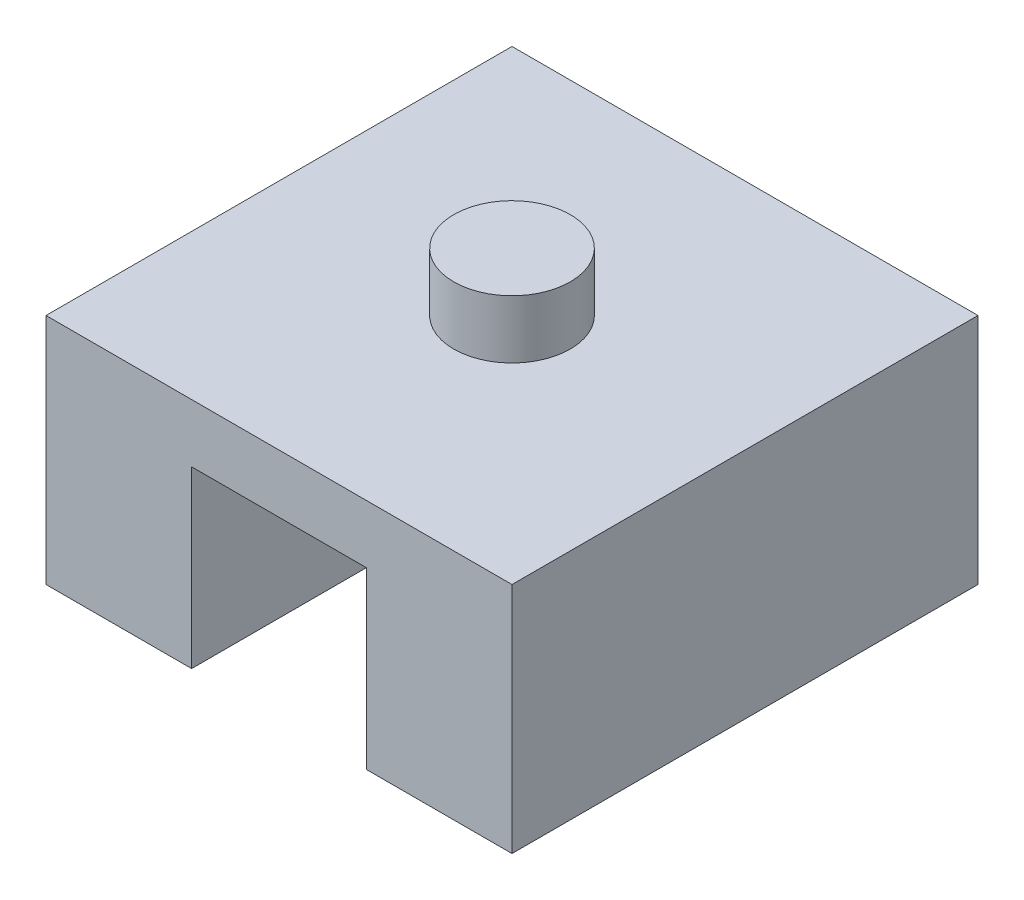
SolidWorks part; units mm, degrees
ref_plane "Front" through (0, 0, 0) normal (0, 0, 1) x (1, 0, 0)
ref_plane "Top" through (0, 0, 0) normal (0, 1, 0) x (1, 0, 0)
ref_plane "Right" through (0, 0, 0) normal (1, 0, 0) x (0, 0, -1)
sketch "Sketch1" plane through (0, 0, 0) normal (0, 0, 1) x (1, 0, 0)
  line L1 (0, 0) -> (50.8, 0)
  line L2 (0, 0) -> (0, 25.4)
  line L3 (0, 25.4) -> (50.8, 25.4)
  line L4 (50.8, 0) -> (50.8, 25.4)
  dimension "D1" = 50.8
  dimension "D2" = 25.4
extrude "Boss-Extrude1" add sketch "Sketch1" along normal blind 50.8
sketch "Sketch2" plane through (0, 0, 50.8) normal (0, 0, 1) x (1, 0, 0)
  line L0 (0, 0) -> (50.8, 0) construction
  line L1 (15.875, 0) -> (34.925, 0)
  line L2 (15.875, 0) -> (15.875, 19.05)
  line L3 (15.875, 19.05) -> (34.925, 19.05)
  line L4 (34.925, 0) -> (34.925, 19.05)
  line L5 (0, 9.525) -> (15.875, 9.525) construction
  line L6 (0, 25.4) -> (0, 0) construction
  line L7 (34.925, 9.525) -> (50.8, 9.525) construction
  line L8 (50.8, 0) -> (50.8, 25.4) construction
  point P14 (0, 0)
  point P15 (0, 0)
  point P16 (0, 0)
  point P17 (0, 0)
  point P18 (0, 0)
  dimension "D1" = 19.05
extrude "Cut-Extrude1" cut sketch "Sketch2" against normal blind 50.8
sketch "Sketch3" plane through (0, 25.4, 0) normal (0, 1, 0) x (1, 0, 0)
  line L0 (0, 0) -> (50.8, -50.8) construction
  circle A0 centre (25.4, -25.4) radius 6.35
  point P6 (0, 0)
  dimension "D1" = 12.7
extrude "Boss-Extrude2" add sketch "Sketch3" along normal blind 6.35
